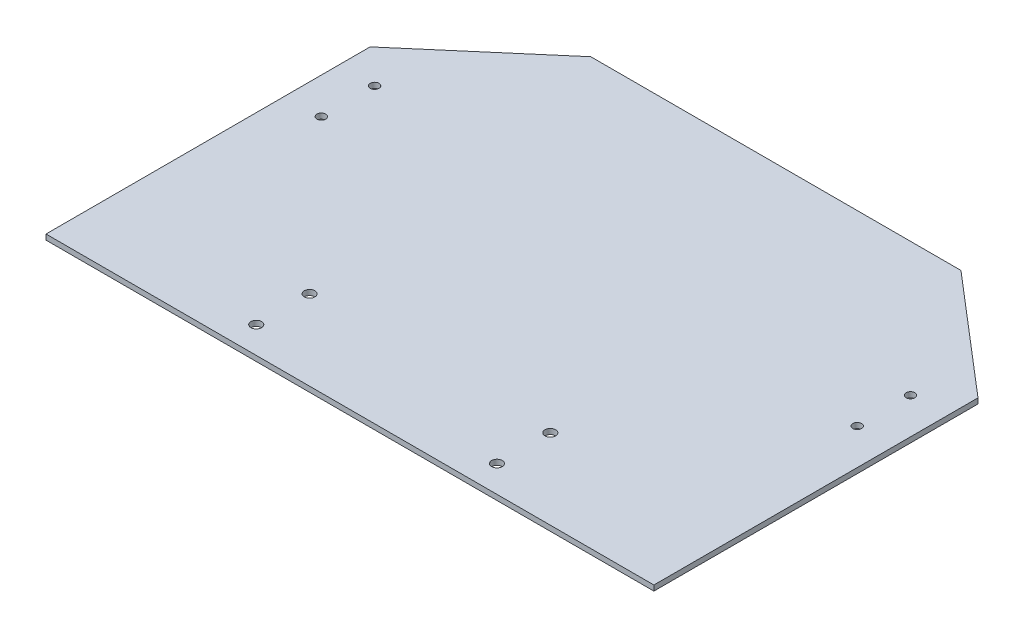
SolidWorks part; units mm, degrees
material "Nylon "
ref_plane "Plano frontal" through (0, 0, 0) normal (0, 0, 1) x (1, 0, 0)
ref_plane "Plano superior" through (0, 0, 0) normal (0, 1, 0) x (1, 0, 0)
ref_plane "Plano direito" through (0, 0, 0) normal (1, 0, 0) x (0, 0, -1)
sketch "Esboço1" plane through (0, 0, 0) normal (0, 1, 0) x (1, 0, 0)
  line L0 (-114, -79.875) -> (114, -79.875)
  line L1 (0, 79.875) -> (0, -79.875)
  line L2 (114, -79.875) -> (114, 41.685)
  line L3 (-69.415, 79.875) -> (69.415, 79.875)
  line L4 (69.415, 79.875) -> (114, 41.685)
  line L5 (-114, -79.875) -> (-114, 41.685)
  line L7 (-69.415, 79.875) -> (-114, 41.685)
  line L8 (51.996, -79.875) -> (51.996, -113.875)
  line L9 (51.996, -113.875) -> (114, -79.875)
  line L10 (-51, -79.875) -> (-51, -113.875)
  line L11 (-51, -113.875) -> (-114, -79.875)
  point P6 (114, -19.095)
  point P7 (0, 0)
  dimension "D1" = 228
  dimension "D2" = 159.75
  dimension "D3" = 121.56
  dimension "D4" = 138.83
  dimension "D5" = 63
  dimension "D6" = 62.004
  dimension "D7" = 34
  dimension "D8" = 34
extrude "Ressalto-extrusão1" add sketch "Esboço1" along normal blind 2 contours L3 L7 L5 L0 L1 | L4 L3 L1 L0 L2
ref_plane "Plano1" through (0, 0, -79.875) normal (0, 0, -1) x (-1, 0, 0)
sketch "Esboço3" plane through (0, 2, 0) normal (0, 1, 0) x (1, 0, 0)
  line L0 (-114, -79.875) -> (-114, 41.685) construction
  line L1 (-114, -79.875) -> (114, -79.875) construction
  line L2 (114, -79.875) -> (114, 41.685) construction
  line L5 (0, -1000) -> (0, 49000) construction
  circle A0 centre (-45.14, -69.875) radius 2
  circle A1 centre (45.14, -69.875) radius 2
  circle A3 centre (-45.14, -49.875) radius 2
  circle A4 centre (45.14, -49.875) radius 2
  point P0 (-45.14, -69.875)
  point P5 (45.14, -69.875)
  dimension "D3" = 4
  dimension "D5" = 4
  dimension "D7" = 20
  dimension "D1" = 68.86
  dimension "D2" = 10
  dimension "D4" = 68.86
  dimension "D6" = 10
extrude "Corte-extrusão2" cut sketch "Esboço3" against normal blind 10
sketch "Esboço4" plane through (0, 2, 0) normal (0, 1, 0) x (1, 0, 0)
  line L8 (-114, -79.875) -> (114, -79.875) construction
  line L10 (-114, 41.685) -> (-114, -79.875)
  line L11 (-114, -79.875) -> (-102.536, -79.875)
  line L12 (-102.536, 75.0881) -> (-102.536, -79.875)
  line L13 (-102.536, 75.0881) -> (-102.536, 86.6244)
  line L15 (114, 41.685) -> (114, -79.875)
  line L16 (114, -79.875) -> (100.6429, -79.875)
  line L17 (100.6429, 75.0881) -> (100.6429, -79.875)
  line L18 (-102.536, 86.6244) -> (-114, 41.685)
  line L19 (100.6429, 75.0881) -> (100.6429, 88.8016)
  line L20 (100.6429, 88.8016) -> (114, 41.685)
extrude "Corte-extrusão4" [suppressed] cut sketch "Esboço4" against normal blind 10
move or copy body "Corpo-Converter em corpo de malha1" [suppressed] bodies to move or copy 110 copy no translate (0, 0, 0) parameters "D1"=0, "D2"=0, "D3"=0
sketch "Esboço5" plane through (0, 2, 0) normal (0, 1, 0) x (1, 0, 0)
  circle A0 centre (100.5, 29.877) radius 1.65
  circle A1 centre (100.5, 9.877) radius 1.65
  circle A2 centre (100.5, 9.877) radius 1.65 construction
  circle A3 centre (100.5, 29.877) radius 1.65 construction
  circle A4 centre (-100.5, 29.877) radius 1.65
  circle A5 centre (-100.5, 9.877) radius 1.65
  circle A6 centre (-100.5, 29.877) radius 1.65 construction
  circle A7 centre (-100.5, 9.877) radius 1.65 construction
extrude "Corte-extrusão5" cut sketch "Esboço5" against normal blind 2
